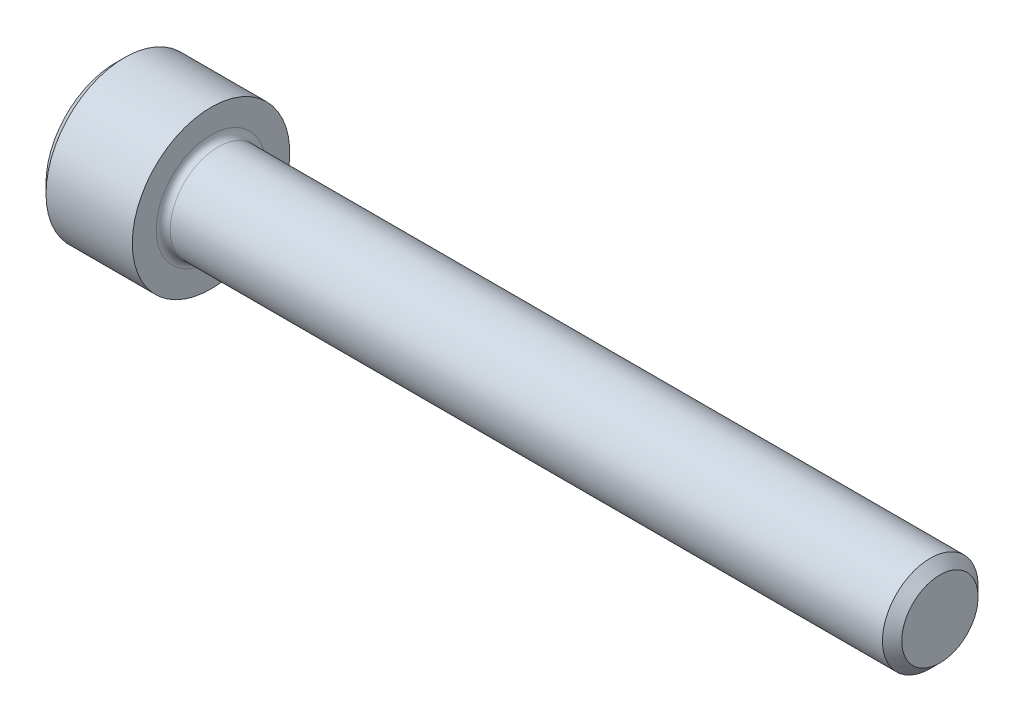
SolidWorks part; units mm, degrees
revolve "Base-Revolve" add sketch "BodySke"
sketch "BodySke" plane through (0, 0, 0) normal (0, 0, 1) x (1, 0, 0)
  line L0 (0, 0) -> (0, 3.0226)
  line L1 (0.4064, 3.429) -> (4.1656, 3.429)
  line L2 (4.1656, 3.429) -> (4.1656, 2.0828)
  line L3 (4.1656, 2.0828) -> (35.4952, 2.0828)
  line L4 (35.9156, 1.6624) -> (35.9156, 0)
  line L5 (35.9156, 0) -> (0, 0)
  line L6 (-31.75, 0) -> (127, 0) construction
  line L7 (0, 3.0226) -> (0.4064, 3.429)
  line L8 (35.9156, 1.6624) -> (35.4952, 2.0828)
  line L9 (0, -3.0226) -> (0.4064, -3.429) construction
  line L10 (35.9156, -1.6624) -> (35.4952, -2.0828) construction
  line L11 (4.8717, 9.525) -> (4.8717, 3.175) construction
  line L12 (13.6906, 9.525) -> (13.6906, 3.175) construction
  line L13 (-2.1844, 9.525) -> (-2.1844, 3.175) construction
  dimension "Diameter" = 4.1656
  dimension "Head_ht" = 4.1656
  dimension "Length" = 31.75
  dimension "Body_ch_ang" = 45
  dimension "Head_dia" = 6.858
  dimension "Head_ch_ang" = 45
  dimension "Head_side_ht" = 3.7592
  dimension "Minor_dia" = 3.3249
  dimension "Advance" = 0.7061
  dimension "Thread_nom" = 22.225
  dimension "Thread_length" = 38.1
cosmetic thread "ThreadCosmetic" [suppressed]
fillet "Fillet1" radius 0.3048 1 edges at (4.1656, 0, 2.0828)
ref_plane "Plane1" through (0, 0, 0) normal (0, 0, 1) x (1, 0, 0)
ref_plane "Plane2" through (0, 0, 0) normal (0, 1, 0) x (1, 0, 0)
ref_plane "Plane3" through (0, 0, 0) normal (1, 0, 0) x (0, 0, -1)
sketch "Sketch2" plane through (0, 0, 0) normal (0, 0, 1) x (1, 0, 0)
  line L0 (0, 1.778) -> (1.9558, 1.778)
  line L1 (1.9558, 1.778) -> (2.9823, 0)
  line L2 (-31.75, 0) -> (127, 0) construction
  line L3 (2.9823, 0) -> (0, 0)
  line L4 (0, 0) -> (0, 1.778)
  line L5 (0, 3.0226) -> (0, -3.0226) construction
  line L6 (0, 0) -> (47.625, 0) construction
  line L7 (4.1656, -3.429) -> (4.1656, 3.429) construction
  dimension "D1" = 1.778
  dimension "D2" = 60
revolve "Hex-PreBroach" cut sketch "Sketch2" angle 360 about L6
sketch "Sketch3" plane through (0, 0, 0) normal (-1, 0, 0) x (0, 0.5, 0.866)
  line L0 (1.0265, 1.778) -> (-1.0265, 1.778)
  line L1 (-1.0265, 1.778) -> (-2.0531, 0)
  line L2 (1.0265, 1.778) -> (2.0531, 0)
  line L3 (1.0265, -1.778) -> (2.0531, 0)
  line L4 (1.0265, -1.778) -> (-1.0265, -1.778)
  line L5 (-1.0265, -1.778) -> (-2.0531, 0)
  dimension "D1" = 1.778
  dimension "D2" = 1.778
  dimension "Hex_size" = 3.556
extrude "Hex" cut sketch "Sketch3" against normal blind 1.9558
sketch "Sketch4" plane through (0, 0, 0) normal (-1, 0, 0) x (0, 0, 1)
  line L0 (0, 0) -> (2.1971, 0)
  line L1 (0, 0) -> (6.1484, 3.5498) construction
  line L2 (0, 0) -> (1.0985, 1.9027)
  line L3 (1.8302, 0.5287) -> (2.0897, 0.6786)
  line L4 (1.373, 1.3206) -> (1.6325, 1.4704)
  arc A0 (1.8302, 0.5287) -> (1.373, 1.3206) centre (0, 0) ccw
  arc A1 (2.1971, 0) -> (2.0897, 0.6786) centre (0, 0) ccw
  arc A2 (1.0985, 1.9027) -> (1.6325, 1.4704) centre (0, 0) cw
  dimension "D1" = 30
  dimension "D2" = 60
  dimension "Spline_p_dim" = 0.9144
  dimension "D3" = 0.4572
extrude "Spline" [suppressed] cut sketch "Sketch4" against normal blind 1.9558
pattern_circular "CirPattern1" [suppressed] count 6 every 60
sketch "Sketch5" plane through (0, 0, 0) normal (0, 0, 1) x (1, 0, 0)
  line L0 (-31.75, 0) -> (127, 0) construction
  line L2 (0, 3.0226) -> (0, -3.0226) construction
  circle A0 centre (1.524, 0) radius 0.5905
  dimension "Drilled_hole_dia" = 1.1811
  dimension "Drilled_hole_loc" = 1.524
extrude "Hole" [suppressed] cut sketch "Sketch5" against normal through all and the other way through all
pattern_circular "Drilled-4" [suppressed] count 2 every 60
pattern_circular "Drilled-6" [suppressed] count 3 every 60
sketch "ThdSchSke" plane through (0, 0, 0) normal (0, 0, 1) x (1, 0, 0)
  line L0 (13.6906, -1.6624) -> (13.3963, -2.0828)
  line L1 (13.6906, -1.6624) -> (13.9849, -2.0828)
  line L2 (13.9849, -2.0828) -> (13.9849, -2.6035)
  line L3 (-3.175, 0) -> (5.1513, 0) construction
  line L5 (13.9849, -2.6035) -> (13.3963, -2.6035)
  line L6 (13.3963, -2.6035) -> (13.3963, -2.0828)
  line L7 (0, 3.0226) -> (0, -3.0226) construction
  dimension "Thread_minor" = 3.3249
  dimension "Diameter" = 4.1656
  dimension "Start" = 13.6906
revolve "ThreadSchematic" [suppressed] cut sketch "ThdSchSke" angle 360 about L3
pattern_linear "ThdSchPat" [suppressed]
equation "\"D2@Sketch3\" = \"Hex_size@Sketch3\" / 2"
equation "\"D1@Sketch3\" = \"Hex_size@Sketch3\" / 2"
equation "\"D1@Sketch2\" = \"Hex_size@Sketch3\" / 2"
equation "\"D3@Sketch4\" = \"Spline_p_dim@Sketch4\" / 2"
equation "\"Thread_minor@ThreadCosmetic\"  =  \"Minor_dia@BodySke\""
equation "\"D2@CirPattern1\" = 360 / \"Num_teeth@CirPattern1\""
equation "\"Wall_thickness@Sketch2\" = \"Head_ht@BodySke\" - \"Key_eng@Hex\""
equation "\"Thread_length@ThreadCosmetic\" = ((sgn( (\"Length@BodySke\" - \"Advance@BodySke\" ) - \"Thread_nom@BodySke\" )-1)*( (\"Length@BodySke\" - \"Advance@BodySke\" ) - \"Thread_nom@BodySke\" ))/-2+ \"Thread_nom@BodySke\""
equation "\"Thread_minor@ThdSchSke\" = \"Minor_dia@BodySke\""
equation "\"Diameter@ThdSchSke\" = \"Diameter@BodySke\""
equation "\"Overcut@ThdSchSke\" = \"Diameter@BodySke\" * 1.25"
equation "\"Start@ThdSchSke\" = \"Head_ht@BodySke\" + \"Length@BodySke\" - \"Thread_length@ThreadCosmetic\"  '---Non-countersunk---"
equation "\"Num_threads@ThdSchPat\" = int( \"Thread_length@ThreadCosmetic\" / \"Advance@BodySke\" + 0.999 )  + 1"
equation "\"Advance@ThdSchPat\" = \"Thread_length@ThreadCosmetic\" /  (\"Num_threads@ThdSchPat\" - 1) 'relax it"
equation "\"Num_threads@ThdSchPat\" = \"Num_threads@ThdSchPat\" - sgn( \"Num_threads@ThdSchPat\" - 1) '---chamfered tips only---"
